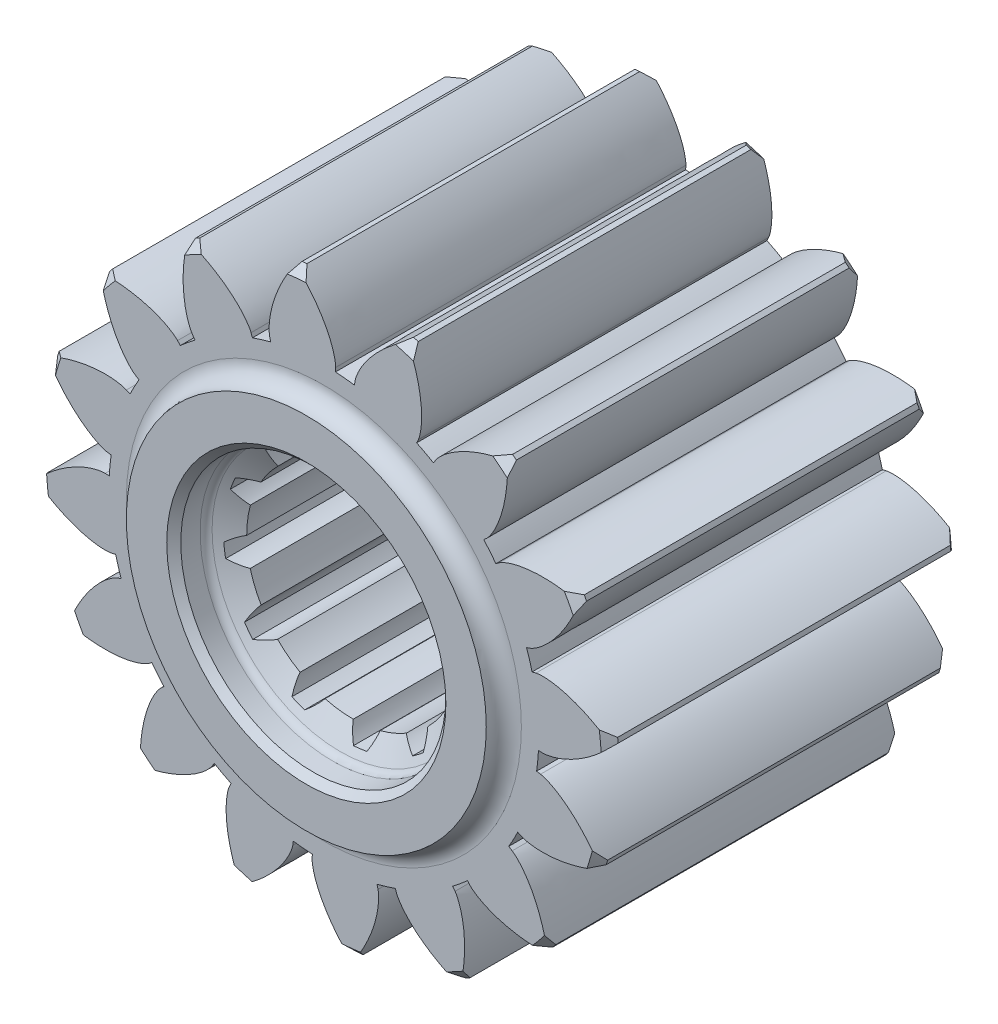
SolidWorks part; units mm, degrees
ref_plane "Front Plane" through (0, 0, 0) normal (0, 0, 1) x (1, 0, 0)
ref_plane "Top Plane" through (0, 0, 0) normal (0, 1, 0) x (1, 0, 0)
ref_plane "Right Plane" through (0, 0, 0) normal (1, 0, 0) x (0, 0, -1)
sketch "Sketch1" plane through (0, 0, 0) normal (1, 0, 0) x (0, 0, -1)
  line L0 (0, 0) -> (43.9, 0) construction
  line L1 (0, 15.9) -> (0, 20.5)
  line L2 (2, 22.5) -> (2, 31.65)
  line L3 (3, 32.65) -> (40.9, 32.65)
  line L4 (41.9, 31.65) -> (41.9, 22.5)
  line L5 (43.9, 20.5) -> (43.9, 15.9)
  line L6 (2, 31.65) -> (3, 32.65)
  line L7 (41.9, 31.65) -> (40.9, 32.65)
  line L8 (0.8, 15.1) -> (3, 15.1)
  line L10 (5.3094, 12.1) -> (38.5906, 12.1)
  line L12 (40.9, 15.1) -> (43.1, 15.1)
  line L13 (0, 15.9) -> (0.8, 15.1)
  line L14 (43.1, 15.1) -> (43.9, 15.9)
  line L15 (3.866, 14.6) -> (5.3094, 12.1)
  line L16 (40.034, 14.6) -> (38.5906, 12.1)
  arc A0 (0, 20.5) -> (2, 22.5) centre (0, 22.5) ccw
  arc A1 (41.9, 22.5) -> (43.9, 20.5) centre (43.9, 22.5) ccw
  arc A2 (3.866, 14.6) -> (3, 15.1) centre (3, 14.1) ccw
  arc A3 (40.9, 15.1) -> (40.034, 14.6) centre (40.9, 14.1) ccw
  dimension "D5" = 2
  dimension "D17" = 1
  dimension "D19" = 3
  dimension "D1" = 43.9
  dimension "D2" = 2
  dimension "D3" = 2
  dimension "D4" = 15.1
  dimension "D6" = 20.5
  dimension "D7" = 32.65
  dimension "D8" = 45
  dimension "D9" = 45
  dimension "D10" = 1
  dimension "D11" = 1
  dimension "D12" = 12.1
  dimension "D13" = 45
  dimension "D14" = 45
  dimension "D15" = 0.8
  dimension "D16" = 0.8
  dimension "D18" = 3
  dimension "D20" = 30
  dimension "D21" = 30
revolve "Revolve1" add sketch "Sketch1" angle 360 about L0
sketch "Sketch2" plane through (0, 0, 0) normal (0, 0, 1) x (1, 0, 0)
  line L0 (0, 0) -> (-1.5655, 11.8974) construction
  arc A0 (-2.5627, 13.5345) -> (-7.7568, 11.3835) centre (0, 0) ccw construction
  arc A1 (3.1074, 11.5907) -> (0, 12) centre (0, 0) ccw construction
  arc A2 (-3.1043, 11.5915) -> (-6, 10.3923) centre (0, 0) ccw construction
  arc A3 (4.5479, 13.0026) -> (-1.0258, 13.7367) centre (0, 0) ccw construction
  arc A4 (8.4864, 8.4842) -> (6, 10.3923) centre (0, 0) ccw construction
  arc A5 (10.4399, 8.9866) -> (5.98, 12.4093) centre (0, 0) ccw construction
  arc A6 (11.5915, 3.1043) -> (10.3923, 6) centre (0, 0) ccw construction
  arc A7 (13.5345, 2.5627) -> (11.3835, 7.7568) centre (0, 0) ccw construction
  arc A8 (11.5907, -3.1074) -> (12, 0) centre (0, 0) ccw construction
  arc A9 (13.0026, -4.5479) -> (13.7367, 1.0258) centre (0, 0) ccw construction
  arc A10 (8.9866, -10.4399) -> (12.4093, -5.98) centre (0, 0) ccw construction
  arc A11 (8.4842, -8.4864) -> (10.3923, -6) centre (0, 0) ccw construction
  arc A12 (3.1043, -11.5915) -> (6, -10.3923) centre (0, 0) ccw construction
  arc A13 (-4.5479, -13.0026) -> (7.7568, -11.3835) centre (0, 0) ccw construction
  arc A14 (-3.1074, -11.5907) -> (0, -12) centre (0, 0) ccw construction
  arc A15 (-8.4864, -8.4842) -> (-6, -10.3923) centre (0, 0) ccw construction
  arc A16 (-10.4399, -8.9866) -> (-5.98, -12.4093) centre (0, 0) ccw construction
  arc A17 (-11.5915, -3.1043) -> (-10.3923, -6) centre (0, 0) ccw construction
  arc A18 (-13.5345, -2.5627) -> (-11.3835, -7.7568) centre (0, 0) ccw construction
  arc A19 (-11.5907, 3.1074) -> (-12, 0) centre (0, 0) ccw construction
  arc A20 (-13.0026, 4.5479) -> (-13.7367, -1.0258) centre (0, 0) ccw construction
  arc A21 (-8.4842, 8.4864) -> (-10.3923, 6) centre (0, 0) ccw construction
  arc A22 (-8.9866, 10.4399) -> (-12.4093, 5.98) centre (0, 0) ccw construction
  circle A23 centre (0, 0) radius 13.775
  circle A24 centre (0, 0) radius 12
  spline S0 degree 3 poles (0, 12) (-0.0366, 12.1032) (-0.1224, 12.3264) (-0.2974, 12.6733) (-0.5245, 13.0595) (-0.7734, 13.4188) (-0.9508, 13.6452) (-1.0258, 13.7367) knots 0.250165 0.250165 0.250165 0.250165 0.360158 0.490165 0.640141 0.810086 0.928975 0.928975 0.928975 0.928975
  spline S1 degree 3 poles (-3.1043, 11.5915) (-3.0956, 11.7007) (-3.0705, 11.9384) (-2.9912, 12.3189) (-2.8717, 12.7507) (-2.7242, 13.1621) (-2.6114, 13.4267) (-2.5627, 13.5345) knots 0.250165 0.250165 0.250165 0.250165 0.360158 0.490165 0.640141 0.810086 0.928975 0.928975 0.928975 0.928975
  spline S2 degree 3 poles (3.1074, 11.5907) (3.1695, 11.6809) (3.3101, 11.8742) (3.569, 12.164) (3.8883, 12.4783) (4.2218, 12.7608) (4.4518, 12.9336) (4.5479, 13.0026) knots 0.250165 0.250165 0.250165 0.250165 0.360158 0.490165 0.640141 0.810086 0.928975 0.928975 0.928975 0.928975
  spline S3 degree 3 poles (6, 10.3923) (6.0199, 10.5) (6.0572, 10.7361) (6.0791, 11.1241) (6.0755, 11.5721) (6.0396, 12.0077) (5.9991, 12.2925) (5.98, 12.4093) knots 0.250165 0.250165 0.250165 0.250165 0.360158 0.490165 0.640141 0.810086 0.928975 0.928975 0.928975 0.928975
  spline S4 degree 3 poles (8.4864, 8.4842) (8.5853, 8.5312) (8.8037, 8.6283) (9.1729, 8.7499) (9.6065, 8.8623) (10.0366, 8.9403) (10.3222, 8.9749) (10.4399, 8.9866) knots 0.250165 0.250165 0.250165 0.250165 0.360158 0.490165 0.640141 0.810086 0.928975 0.928975 0.928975 0.928975
  spline S5 degree 3 poles (10.3923, 6) (10.4633, 6.0833) (10.6138, 6.2692) (10.8267, 6.5942) (11.0476, 6.984) (11.2343, 7.3792) (11.3417, 7.6461) (11.3835, 7.7568) knots 0.250165 0.250165 0.250165 0.250165 0.360158 0.490165 0.640141 0.810086 0.928975 0.928975 0.928975 0.928975
  spline S6 degree 3 poles (11.5915, 3.1043) (11.7007, 3.0956) (11.9384, 3.0705) (12.3189, 2.9912) (12.7507, 2.8717) (13.1621, 2.7242) (13.4267, 2.6114) (13.5345, 2.5627) knots 0.250165 0.250165 0.250165 0.250165 0.360158 0.490165 0.640141 0.810086 0.928975 0.928975 0.928975 0.928975
  spline S7 degree 3 poles (12, 0) (12.1032, 0.0366) (12.3264, 0.1224) (12.6733, 0.2974) (13.0595, 0.5245) (13.4188, 0.7734) (13.6452, 0.9508) (13.7367, 1.0258) knots 0.250165 0.250165 0.250165 0.250165 0.360158 0.490165 0.640141 0.810086 0.928975 0.928975 0.928975 0.928975
  spline S8 degree 3 poles (11.5907, -3.1074) (11.6809, -3.1695) (11.8742, -3.3101) (12.164, -3.569) (12.4783, -3.8883) (12.7608, -4.2218) (12.9336, -4.4518) (13.0026, -4.5479) knots 0.250165 0.250165 0.250165 0.250165 0.360158 0.490165 0.640141 0.810086 0.928975 0.928975 0.928975 0.928975
  spline S9 degree 3 poles (10.3923, -6) (10.5, -6.0199) (10.7361, -6.0572) (11.1241, -6.0791) (11.5721, -6.0755) (12.0077, -6.0396) (12.2925, -5.9991) (12.4093, -5.98) knots 0.250165 0.250165 0.250165 0.250165 0.360158 0.490165 0.640141 0.810086 0.928975 0.928975 0.928975 0.928975
  spline S10 degree 3 poles (8.4842, -8.4864) (8.5312, -8.5853) (8.6283, -8.8037) (8.7499, -9.1729) (8.8623, -9.6065) (8.9403, -10.0366) (8.9749, -10.3222) (8.9866, -10.4399) knots 0.250165 0.250165 0.250165 0.250165 0.360158 0.490165 0.640141 0.810086 0.928975 0.928975 0.928975 0.928975
  spline S11 degree 3 poles (6, -10.3923) (6.0833, -10.4633) (6.2692, -10.6138) (6.5942, -10.8267) (6.984, -11.0476) (7.3792, -11.2343) (7.6461, -11.3417) (7.7568, -11.3835) knots 0.250165 0.250165 0.250165 0.250165 0.360158 0.490165 0.640141 0.810086 0.928975 0.928975 0.928975 0.928975
  spline S12 degree 3 poles (3.1043, -11.5915) (3.0956, -11.7007) (3.0705, -11.9384) (2.9912, -12.3189) (2.8717, -12.7507) (2.7242, -13.1621) (2.6114, -13.4267) (2.5627, -13.5345) knots 0.250165 0.250165 0.250165 0.250165 0.360158 0.490165 0.640141 0.810086 0.928975 0.928975 0.928975 0.928975
  spline S13 degree 3 poles (0, -12) (0.0366, -12.1032) (0.1224, -12.3264) (0.2974, -12.6733) (0.5245, -13.0595) (0.7734, -13.4188) (0.9508, -13.6452) (1.0258, -13.7367) knots 0.250165 0.250165 0.250165 0.250165 0.360158 0.490165 0.640141 0.810086 0.928975 0.928975 0.928975 0.928975
  spline S14 degree 3 poles (-3.1074, -11.5907) (-3.1695, -11.6809) (-3.3101, -11.8742) (-3.569, -12.164) (-3.8883, -12.4783) (-4.2218, -12.7608) (-4.4518, -12.9336) (-4.5479, -13.0026) knots 0.250165 0.250165 0.250165 0.250165 0.360158 0.490165 0.640141 0.810086 0.928975 0.928975 0.928975 0.928975
  spline S15 degree 3 poles (-6, -10.3923) (-6.0199, -10.5) (-6.0572, -10.7361) (-6.0791, -11.1241) (-6.0755, -11.5721) (-6.0396, -12.0077) (-5.9991, -12.2925) (-5.98, -12.4093) knots 0.250165 0.250165 0.250165 0.250165 0.360158 0.490165 0.640141 0.810086 0.928975 0.928975 0.928975 0.928975
  spline S16 degree 3 poles (-8.4864, -8.4842) (-8.5853, -8.5312) (-8.8037, -8.6283) (-9.1729, -8.7499) (-9.6065, -8.8623) (-10.0366, -8.9403) (-10.3222, -8.9749) (-10.4399, -8.9866) knots 0.250165 0.250165 0.250165 0.250165 0.360158 0.490165 0.640141 0.810086 0.928975 0.928975 0.928975 0.928975
  spline S17 degree 3 poles (-10.3923, -6) (-10.4633, -6.0833) (-10.6138, -6.2692) (-10.8267, -6.5942) (-11.0476, -6.984) (-11.2343, -7.3792) (-11.3417, -7.6461) (-11.3835, -7.7568) knots 0.250165 0.250165 0.250165 0.250165 0.360158 0.490165 0.640141 0.810086 0.928975 0.928975 0.928975 0.928975
  spline S18 degree 3 poles (-11.5915, -3.1043) (-11.7007, -3.0956) (-11.9384, -3.0705) (-12.3189, -2.9912) (-12.7507, -2.8717) (-13.1621, -2.7242) (-13.4267, -2.6114) (-13.5345, -2.5627) knots 0.250165 0.250165 0.250165 0.250165 0.360158 0.490165 0.640141 0.810086 0.928975 0.928975 0.928975 0.928975
  spline S19 degree 3 poles (-12, 0) (-12.1032, -0.0366) (-12.3264, -0.1224) (-12.6733, -0.2974) (-13.0595, -0.5245) (-13.4188, -0.7734) (-13.6452, -0.9508) (-13.7367, -1.0258) knots 0.250165 0.250165 0.250165 0.250165 0.360158 0.490165 0.640141 0.810086 0.928975 0.928975 0.928975 0.928975
  spline S20 degree 3 poles (-11.5907, 3.1074) (-11.6809, 3.1695) (-11.8742, 3.3101) (-12.164, 3.569) (-12.4783, 3.8883) (-12.7608, 4.2218) (-12.9336, 4.4518) (-13.0026, 4.5479) knots 0.250165 0.250165 0.250165 0.250165 0.360158 0.490165 0.640141 0.810086 0.928975 0.928975 0.928975 0.928975
  spline S21 degree 3 poles (-10.3923, 6) (-10.5, 6.0199) (-10.7361, 6.0572) (-11.1241, 6.0791) (-11.5721, 6.0755) (-12.0077, 6.0396) (-12.2925, 5.9991) (-12.4093, 5.98) knots 0.250165 0.250165 0.250165 0.250165 0.360158 0.490165 0.640141 0.810086 0.928975 0.928975 0.928975 0.928975
  spline S22 degree 3 poles (-8.4842, 8.4864) (-8.5312, 8.5853) (-8.6283, 8.8037) (-8.7499, 9.1729) (-8.8623, 9.6065) (-8.9403, 10.0366) (-8.9749, 10.3222) (-8.9866, 10.4399) knots 0.250165 0.250165 0.250165 0.250165 0.360158 0.490165 0.640141 0.810086 0.928975 0.928975 0.928975 0.928975
  spline S23 degree 3 poles (-6, 10.3923) (-6.0833, 10.4633) (-6.2692, 10.6138) (-6.5942, 10.8267) (-6.984, 11.0476) (-7.3792, 11.2343) (-7.6461, 11.3417) (-7.7568, 11.3835) knots 0.250165 0.250165 0.250165 0.250165 0.360158 0.490165 0.640141 0.810086 0.928975 0.928975 0.928975 0.928975
  point P146 (0, 0)
  dimension "D1" = 27.55
  dimension "D2" = 1.57
extrude "Cut-Extrude1" cut sketch "Sketch2" against normal through all contours A24 S23 A23 S22 | A24 S21 A23 S20 | A24 S19 A23 S18 | A24 S17 A23 S16 | A24 S15 A23 S14 | A24 S13 A23 S12 | A24 S11 A23 S10 | A24 S9 A23 S8 | A24 S7 A23 S6 | A24 S5 A23 S4 | A24 S3 A23 S2 | S1 A24 S0 A23
sketch "Sketch3" plane through (0, 0, 0) normal (0, 0, 1) x (1, 0, 0)
  line L0 (-23.9037, 28.8) -> (23.9037, 28.8) construction
  line L1 (0, 28.8) -> (21.2128, 41.0472) construction
  line L2 (0, 28.8) -> (-37.797, 6.9779) construction
  line L3 (0, 0) -> (-12.4708, 21.6) construction
  line L4 (0, 0) -> (0, 28.8) construction
  line L5 (0, 0) -> (-7.1956, 23.881) construction
  line L6 (0, 0) -> (-4.3963, 24.551) construction
  line L7 (0, 0) -> (-9.8991, 22.893) construction
  line L8 (0, 0) -> (-1.5384, 24.894) construction
  line L9 (0, 0) -> (1.34, 24.9055) construction
  line L10 (-9.8991, 22.893) -> (0.6747, 27.4652) construction
  line L11 (-7.1956, 23.881) -> (1.077, 26.3737) construction
  line L12 (-4.3963, 24.551) -> (1.2735, 25.5663) construction
  line L13 (-1.5384, 24.894) -> (1.3361, 25.0717) construction
  circle A0 centre (0, 0) radius 28.8 construction
  circle A1 centre (0, 0) radius 24.9415 construction
  point P6 (0, 28.8)
  point P14 (-7.4825, 24.48)
  point P17 (-4.9883, 25.92)
  point P18 (-9.9766, 23.04)
  point P19 (-2.4942, 27.36)
  dimension "D1" = 57.6
  dimension "D2" = 30
  dimension "D3" = 14.4
  dimension "D4" = 2.88
  dimension "D5" = 2.88
  dimension "D6" = 2.88
  dimension "D7" = 2.88
  dimension "D8" = 2.88
  dimension "D9" = 5.76
  dimension "D10" = 8.64
  dimension "D11" = 11.52
  dimension "D17" = 11.52
  dimension "D18" = 8.64
  dimension "D19" = 5.76
  dimension "D20" = 2.88
  dimension "D12" = 2.88
  dimension "D13" = 2.88
  dimension "D14" = 2.88
  dimension "D15" = 2.88
  dimension "D16" = 2.88
sketch "Sketch4" plane through (0, 0, 0) normal (0, 0, 1) x (1, 0, 0)
  line L0 (-14.8763, 20.0194) -> (0, 0) construction
  line L2 (0, 0) -> (-17.0838, 18.1721) construction
  line L3 (-19.0637, 16.0828) -> (0, 0) construction
  line L4 (0, 0) -> (-20.7897, 13.7793) construction
  line L5 (0, 0) -> (-22.2388, 11.2923) construction
  line L6 (0, 28.8) -> (-37.797, 6.9779) construction
  line L7 (-14.8763, 20.0194) -> (-1.0065, 30.326) construction
  line L8 (-17.0838, 18.1721) -> (-2.3954, 31.9807) construction
  line L9 (-19.0637, 16.0828) -> (-4.207, 33.6931) construction
  line L10 (-20.7897, 13.7793) -> (-6.4698, 35.3846) construction
  line L11 (-22.2388, 11.2923) -> (-9.1996, 36.9714) construction
  circle A0 centre (0, 0) radius 24.9415 construction
  circle A1 centre (0, 0) radius 28.8 construction
  point P8 (-24.9415, 14.4)
  point P11 (-22.4474, 15.84)
  point P16 (-19.9532, 17.28)
  point P17 (-17.4591, 18.72)
  point P18 (-14.9649, 20.16)
  dimension "D4" = 2.88
  dimension "D5" = 2.88
  dimension "D6" = 2.88
  dimension "D7" = 2.88
  dimension "D1" = 14.4
  dimension "D2" = 2.88
  dimension "D3" = 2.88
  dimension "D12" = 17.28
  dimension "D13" = 20.16
  dimension "D14" = 23.04
  dimension "D15" = 25.92
  dimension "D16" = 28.8
  dimension "D17" = 17.28
  dimension "D18" = 20.16
  dimension "D19" = 23.04
  dimension "D20" = 25.92
  dimension "D21" = 28.8
  dimension "D8" = 2.88
  dimension "D9" = 2.88
  dimension "D10" = 2.88
  dimension "D11" = 2.88
sketch "Sketch5" plane through (0, 0, 0) normal (0, 0, 1) x (1, 0, 0)
  line L0 (1.3152, 24.4446) -> (1.34, 24.9055)
  line L1 (0, 0) -> (-2.8215, 28.6615) construction
  line L2 (3.4814, 24.2312) -> (3.547, 24.688)
  line L3 (-6.0565, 23.719) -> (-6.1707, 24.1662)
  line L4 (10.5696, 22.0806) -> (10.7689, 22.4969)
  line L5 (12.4893, 21.0544) -> (12.7247, 21.4514)
  line L6 (18.215, 16.355) -> (18.5584, 16.6633)
  line L7 (19.5958, 14.6723) -> (19.9652, 14.9489)
  line L8 (23.0872, 8.1395) -> (23.5225, 8.2929)
  line L9 (23.719, 6.0565) -> (24.1662, 6.1707)
  line L10 (24.4446, -1.3152) -> (24.9055, -1.34)
  line L11 (24.2312, -3.4814) -> (24.688, -3.547)
  line L12 (22.0806, -10.5696) -> (22.4969, -10.7689)
  line L13 (21.0544, -12.4893) -> (21.4514, -12.7247)
  line L14 (16.355, -18.215) -> (16.6633, -18.5584)
  line L15 (14.6723, -19.5958) -> (14.9489, -19.9652)
  line L16 (8.1395, -23.0872) -> (8.2929, -23.5225)
  line L17 (6.0565, -23.719) -> (6.1707, -24.1662)
  line L18 (-1.3152, -24.4446) -> (-1.34, -24.9055)
  line L19 (-3.4814, -24.2312) -> (-3.547, -24.688)
  line L20 (-10.5696, -22.0806) -> (-10.7689, -22.4969)
  line L21 (-12.4893, -21.0544) -> (-12.7247, -21.4514)
  line L22 (-18.215, -16.355) -> (-18.5584, -16.6633)
  line L23 (-19.5958, -14.6723) -> (-19.9652, -14.9489)
  line L24 (-23.0872, -8.1395) -> (-23.5225, -8.2929)
  line L25 (-23.719, -6.0565) -> (-24.1662, -6.1707)
  line L26 (-24.4446, 1.3152) -> (-24.9055, 1.34)
  line L27 (-24.2312, 3.4814) -> (-24.688, 3.547)
  line L28 (-22.0806, 10.5696) -> (-22.4969, 10.7689)
  line L29 (-21.0544, 12.4893) -> (-21.4514, 12.7247)
  line L30 (-16.355, 18.215) -> (-16.6633, 18.5584)
  line L31 (-14.6723, 19.5958) -> (-14.9489, 19.9652)
  line L32 (-8.1395, 23.0872) -> (-8.2929, 23.5225)
  line L33 (0, 0) -> (0, 32.65) construction
  circle A0 centre (0, 0) radius 32.65
  circle A1 centre (0, 0) radius 24.48
  circle A2 centre (0, 0) radius 28.8 construction
  spline S0 degree 3 poles (1.34, 24.9055) (1.3422, 25.1274) (1.2774, 25.6238) (1.063, 26.4852) (0.6532, 27.5769) (-0.0282, 28.9119) (-1.0423, 30.4377) (-2.0639, 31.6476) (-2.7423, 32.3428) (-2.9205, 32.5191) knots 0 0 0 0 0.040002 0.090002 0.160002 0.250002 0.360002 0.490002 0.535233 0.535233 0.535233 0.535233
  spline S1 degree 3 poles (-6.1707, 24.1662) (-6.2161, 24.3833) (-6.2493, 24.8829) (-6.207, 25.7695) (-6.018, 26.9202) (-5.6099, 28.3624) (-4.9128, 30.0567) (-4.1468, 31.4426) (-3.617, 32.2567) (-3.4765, 32.4644) knots 0 0 0 0 0.040002 0.090002 0.160002 0.250002 0.360002 0.490002 0.535233 0.535233 0.535233 0.535233
  spline S2 degree 3 poles (3.547, 24.688) (3.5882, 24.906) (3.7487, 25.3803) (4.1271, 26.1832) (4.742, 27.174) (5.6709, 28.3502) (6.9634, 29.6488) (8.2014, 30.6361) (9.0025, 31.1855) (9.2117, 31.3236) knots 0 0 0 0 0.040002 0.090002 0.160002 0.250002 0.360002 0.490002 0.535233 0.535233 0.535233 0.535233
  spline S3 degree 3 poles (10.7689, 22.4969) (10.8558, 22.701) (10.9859, 23.1845) (11.1175, 24.0623) (11.1567, 25.2278) (11.038, 26.7219) (10.685, 28.5197) (10.2042, 30.0284) (9.8435, 30.9303) (9.7463, 31.1614) knots 0 0 0 0 0.040002 0.090002 0.160002 0.250002 0.360002 0.490002 0.535233 0.535233 0.535233 0.535233
  spline S4 degree 3 poles (12.7247, 21.4514) (12.8462, 21.637) (13.1759, 22.0138) (13.8328, 22.6108) (14.7801, 23.2908) (16.0884, 24.022) (17.7794, 24.7272) (19.3011, 25.1655) (20.2514, 25.3665) (20.4975, 25.4141) knots 0 0 0 0 0.040002 0.090002 0.160002 0.250002 0.360002 0.490002 0.535233 0.535233 0.535233 0.535233
  spline S5 degree 3 poles (18.5584, 16.6633) (18.7168, 16.8187) (19.022, 17.2155) (19.4795, 17.9762) (19.9617, 19.0379) (20.4238, 20.4637) (20.7857, 22.2598) (20.9189, 23.8376) (20.9308, 24.8089) (20.9294, 25.0596) knots 0 0 0 0 0.040002 0.090002 0.160002 0.250002 0.360002 0.490002 0.535233 0.535233 0.535233 0.535233
  spline S6 degree 3 poles (19.9652, 14.9489) (20.1485, 15.074) (20.5973, 15.2959) (21.4326, 15.5961) (22.5681, 15.8618) (24.0566, 16.0367) (25.8887, 16.041) (27.4623, 15.8637) (28.4172, 15.6858) (28.6628, 15.6355) knots 0 0 0 0 0.040002 0.090002 0.160002 0.250002 0.360002 0.490002 0.535233 0.535233 0.535233 0.535233
  spline S7 degree 3 poles (23.5225, 8.2929) (23.7283, 8.3758) (24.1621, 8.6257) (24.8759, 9.1534) (25.7278, 9.9497) (26.7003, 11.0902) (27.7219, 12.611) (28.4488, 14.0178) (28.8315, 14.9106) (28.9261, 15.1428) knots 0 0 0 0 0.040002 0.090002 0.160002 0.250002 0.360002 0.490002 0.535233 0.535233 0.535233 0.535233
  spline S8 degree 3 poles (24.1662, 6.1707) (24.3833, 6.2161) (24.8829, 6.2493) (25.7695, 6.207) (26.9202, 6.018) (28.3624, 5.6099) (30.0567, 4.9128) (31.4426, 4.1468) (32.2567, 3.617) (32.4644, 3.4765) knots 0 0 0 0 0.040002 0.090002 0.160002 0.250002 0.360002 0.490002 0.535233 0.535233 0.535233 0.535233
  spline S9 degree 3 poles (24.9055, -1.34) (25.1274, -1.3422) (25.6238, -1.2774) (26.4852, -1.063) (27.5769, -0.6532) (28.9119, 0.0282) (30.4377, 1.0423) (31.6476, 2.0639) (32.3428, 2.7423) (32.5191, 2.9205) knots 0 0 0 0 0.040002 0.090002 0.160002 0.250002 0.360002 0.490002 0.535233 0.535233 0.535233 0.535233
  spline S10 degree 3 poles (24.688, -3.547) (24.906, -3.5882) (25.3803, -3.7487) (26.1832, -4.1271) (27.174, -4.742) (28.3502, -5.6709) (29.6488, -6.9634) (30.6361, -8.2014) (31.1855, -9.0025) (31.3236, -9.2117) knots 0 0 0 0 0.040002 0.090002 0.160002 0.250002 0.360002 0.490002 0.535233 0.535233 0.535233 0.535233
  spline S11 degree 3 poles (22.4969, -10.7689) (22.701, -10.8558) (23.1845, -10.9859) (24.0623, -11.1175) (25.2278, -11.1567) (26.7219, -11.038) (28.5197, -10.685) (30.0284, -10.2042) (30.9303, -9.8435) (31.1614, -9.7463) knots 0 0 0 0 0.040002 0.090002 0.160002 0.250002 0.360002 0.490002 0.535233 0.535233 0.535233 0.535233
  spline S12 degree 3 poles (21.4514, -12.7247) (21.637, -12.8462) (22.0138, -13.1759) (22.6108, -13.8328) (23.2908, -14.7801) (24.022, -16.0884) (24.7272, -17.7794) (25.1655, -19.3011) (25.3665, -20.2514) (25.4141, -20.4975) knots 0 0 0 0 0.040002 0.090002 0.160002 0.250002 0.360002 0.490002 0.535233 0.535233 0.535233 0.535233
  spline S13 degree 3 poles (16.6633, -18.5584) (16.8187, -18.7168) (17.2155, -19.022) (17.9762, -19.4795) (19.0379, -19.9617) (20.4637, -20.4238) (22.2598, -20.7857) (23.8376, -20.9189) (24.8089, -20.9308) (25.0596, -20.9294) knots 0 0 0 0 0.040002 0.090002 0.160002 0.250002 0.360002 0.490002 0.535233 0.535233 0.535233 0.535233
  spline S14 degree 3 poles (14.9489, -19.9652) (15.074, -20.1485) (15.2959, -20.5973) (15.5961, -21.4326) (15.8618, -22.5681) (16.0367, -24.0566) (16.041, -25.8887) (15.8637, -27.4623) (15.6858, -28.4172) (15.6355, -28.6628) knots 0 0 0 0 0.040002 0.090002 0.160002 0.250002 0.360002 0.490002 0.535233 0.535233 0.535233 0.535233
  spline S15 degree 3 poles (8.2929, -23.5225) (8.3758, -23.7283) (8.6257, -24.1621) (9.1534, -24.8759) (9.9497, -25.7278) (11.0902, -26.7003) (12.611, -27.7219) (14.0178, -28.4488) (14.9106, -28.8315) (15.1428, -28.9261) knots 0 0 0 0 0.040002 0.090002 0.160002 0.250002 0.360002 0.490002 0.535233 0.535233 0.535233 0.535233
  spline S16 degree 3 poles (6.1707, -24.1662) (6.2161, -24.3833) (6.2493, -24.8829) (6.207, -25.7695) (6.018, -26.9202) (5.6099, -28.3624) (4.9128, -30.0567) (4.1468, -31.4426) (3.617, -32.2567) (3.4765, -32.4644) knots 0 0 0 0 0.040002 0.090002 0.160002 0.250002 0.360002 0.490002 0.535233 0.535233 0.535233 0.535233
  spline S17 degree 3 poles (-1.34, -24.9055) (-1.3422, -25.1274) (-1.2774, -25.6238) (-1.063, -26.4852) (-0.6532, -27.5769) (0.0282, -28.9119) (1.0423, -30.4377) (2.0639, -31.6476) (2.7423, -32.3428) (2.9205, -32.5191) knots 0 0 0 0 0.040002 0.090002 0.160002 0.250002 0.360002 0.490002 0.535233 0.535233 0.535233 0.535233
  spline S18 degree 3 poles (-3.547, -24.688) (-3.5882, -24.906) (-3.7487, -25.3803) (-4.1271, -26.1832) (-4.742, -27.174) (-5.6709, -28.3502) (-6.9634, -29.6488) (-8.2014, -30.6361) (-9.0025, -31.1855) (-9.2117, -31.3236) knots 0 0 0 0 0.040002 0.090002 0.160002 0.250002 0.360002 0.490002 0.535233 0.535233 0.535233 0.535233
  spline S19 degree 3 poles (-10.7689, -22.4969) (-10.8558, -22.701) (-10.9859, -23.1845) (-11.1175, -24.0623) (-11.1567, -25.2278) (-11.038, -26.7219) (-10.685, -28.5197) (-10.2042, -30.0284) (-9.8435, -30.9303) (-9.7463, -31.1614) knots 0 0 0 0 0.040002 0.090002 0.160002 0.250002 0.360002 0.490002 0.535233 0.535233 0.535233 0.535233
  spline S20 degree 3 poles (-12.7247, -21.4514) (-12.8462, -21.637) (-13.1759, -22.0138) (-13.8328, -22.6108) (-14.7801, -23.2908) (-16.0884, -24.022) (-17.7794, -24.7272) (-19.3011, -25.1655) (-20.2514, -25.3665) (-20.4975, -25.4141) knots 0 0 0 0 0.040002 0.090002 0.160002 0.250002 0.360002 0.490002 0.535233 0.535233 0.535233 0.535233
  spline S21 degree 3 poles (-18.5584, -16.6633) (-18.7168, -16.8187) (-19.022, -17.2155) (-19.4795, -17.9762) (-19.9617, -19.0379) (-20.4238, -20.4637) (-20.7857, -22.2598) (-20.9189, -23.8376) (-20.9308, -24.8089) (-20.9294, -25.0596) knots 0 0 0 0 0.040002 0.090002 0.160002 0.250002 0.360002 0.490002 0.535233 0.535233 0.535233 0.535233
  spline S22 degree 3 poles (-19.9652, -14.9489) (-20.1485, -15.074) (-20.5973, -15.2959) (-21.4326, -15.5961) (-22.5681, -15.8618) (-24.0566, -16.0367) (-25.8887, -16.041) (-27.4623, -15.8637) (-28.4172, -15.6858) (-28.6628, -15.6355) knots 0 0 0 0 0.040002 0.090002 0.160002 0.250002 0.360002 0.490002 0.535233 0.535233 0.535233 0.535233
  spline S23 degree 3 poles (-23.5225, -8.2929) (-23.7283, -8.3758) (-24.1621, -8.6257) (-24.8759, -9.1534) (-25.7278, -9.9497) (-26.7003, -11.0902) (-27.7219, -12.611) (-28.4488, -14.0178) (-28.8315, -14.9106) (-28.9261, -15.1428) knots 0 0 0 0 0.040002 0.090002 0.160002 0.250002 0.360002 0.490002 0.535233 0.535233 0.535233 0.535233
  spline S24 degree 3 poles (-24.1662, -6.1707) (-24.3833, -6.2161) (-24.8829, -6.2493) (-25.7695, -6.207) (-26.9202, -6.018) (-28.3624, -5.6099) (-30.0567, -4.9128) (-31.4426, -4.1468) (-32.2567, -3.617) (-32.4644, -3.4765) knots 0 0 0 0 0.040002 0.090002 0.160002 0.250002 0.360002 0.490002 0.535233 0.535233 0.535233 0.535233
  spline S25 degree 3 poles (-24.9055, 1.34) (-25.1274, 1.3422) (-25.6238, 1.2774) (-26.4852, 1.063) (-27.5769, 0.6532) (-28.9119, -0.0282) (-30.4377, -1.0423) (-31.6476, -2.0639) (-32.3428, -2.7423) (-32.5191, -2.9205) knots 0 0 0 0 0.040002 0.090002 0.160002 0.250002 0.360002 0.490002 0.535233 0.535233 0.535233 0.535233
  spline S26 degree 3 poles (-24.688, 3.547) (-24.906, 3.5882) (-25.3803, 3.7487) (-26.1832, 4.1271) (-27.174, 4.742) (-28.3502, 5.6709) (-29.6488, 6.9634) (-30.6361, 8.2014) (-31.1855, 9.0025) (-31.3236, 9.2117) knots 0 0 0 0 0.040002 0.090002 0.160002 0.250002 0.360002 0.490002 0.535233 0.535233 0.535233 0.535233
  spline S27 degree 3 poles (-22.4969, 10.7689) (-22.701, 10.8558) (-23.1845, 10.9859) (-24.0623, 11.1175) (-25.2278, 11.1567) (-26.7219, 11.038) (-28.5197, 10.685) (-30.0284, 10.2042) (-30.9303, 9.8435) (-31.1614, 9.7463) knots 0 0 0 0 0.040002 0.090002 0.160002 0.250002 0.360002 0.490002 0.535233 0.535233 0.535233 0.535233
  spline S28 degree 3 poles (-21.4514, 12.7247) (-21.637, 12.8462) (-22.0138, 13.1759) (-22.6108, 13.8328) (-23.2908, 14.7801) (-24.022, 16.0884) (-24.7272, 17.7794) (-25.1655, 19.3011) (-25.3665, 20.2514) (-25.4141, 20.4975) knots 0 0 0 0 0.040002 0.090002 0.160002 0.250002 0.360002 0.490002 0.535233 0.535233 0.535233 0.535233
  spline S29 degree 3 poles (-16.6633, 18.5584) (-16.8187, 18.7168) (-17.2155, 19.022) (-17.9762, 19.4795) (-19.0379, 19.9617) (-20.4637, 20.4238) (-22.2598, 20.7857) (-23.8376, 20.9189) (-24.8089, 20.9308) (-25.0596, 20.9294) knots 0 0 0 0 0.040002 0.090002 0.160002 0.250002 0.360002 0.490002 0.535233 0.535233 0.535233 0.535233
  spline S30 degree 3 poles (-14.9489, 19.9652) (-15.074, 20.1485) (-15.2959, 20.5973) (-15.5961, 21.4326) (-15.8618, 22.5681) (-16.0367, 24.0566) (-16.041, 25.8887) (-15.8637, 27.4623) (-15.6858, 28.4172) (-15.6355, 28.6628) knots 0 0 0 0 0.040002 0.090002 0.160002 0.250002 0.360002 0.490002 0.535233 0.535233 0.535233 0.535233
  spline S31 degree 3 poles (-8.2929, 23.5225) (-8.3758, 23.7283) (-8.6257, 24.1621) (-9.1534, 24.8759) (-9.9497, 25.7278) (-11.0902, 26.7003) (-12.611, 27.7219) (-14.0178, 28.4488) (-14.9106, 28.8315) (-15.1428, 28.9261) knots 0 0 0 0 0.040002 0.090002 0.160002 0.250002 0.360002 0.490002 0.535233 0.535233 0.535233 0.535233
  point P340 (0, 0)
  dimension "D1" = 65.3
  dimension "D2" = 48.96
  dimension "D5" = 5.622
  dimension "D3" = 2.826
  dimension "D4" = 16
extrude "Cut-Extrude2" cut sketch "Sketch5" against normal through all contours L2 S2 A0 S0 L0 A1 | S31 L32 A1 L3 S1 A0 | L31 S30 A0 S29 L30 A1 | L29 S28 A0 S27 L28 A1 | L27 S26 A0 S25 L26 A1 | L25 S24 A0 S23 L24 A1 | L23 S22 A0 S21 L22 A1 | L21 S20 A0 S19 L20 A1 | L19 S18 A0 S17 L18 A1 | L17 S16 A0 S15 L16 A1 | L15 S14 A0 S13 L14 A1 | L13 S12 A0 S11 L12 A1 | L11 S10 A0 S9 L10 A1 | L9 S8 A0 S7 L8 A1 | L7 S6 A0 S5 L6 A1 | L5 S4 A0 S3 L4 A1
equation "\"Z\"= 16'No of Teeth"
equation "\"m\"= 3.6'Module"
equation "\"a\"= 30'Pressure angle"
equation "\"d0\"= \"m\" * \"Z\"'Mid diameter"
equation "\"hk\"= \"m\""
equation "\"hf\"= \"m\" * 1.2"
equation "\"da\"= \"d0\" + \"m\" * 2 + 0.5'outer diameter"
equation "\"df\"= \"d0\" - \"hf\" * 2'root diameter"
equation "\"S\"= ( \"m\" * 3.14 ) / 2"
equation "\"D1@Sketch3\"=\"d0\""
equation "\"D2@Sketch3\"=\"a\""
equation "\"D5@Sketch3\"=\"D4@Sketch3\""
equation "\"D6@Sketch3\"=\"D4@Sketch3\""
equation "\"D7@Sketch3\"=\"D4@Sketch3\""
equation "\"D12@Sketch3\"=\"D4@Sketch3\""
equation "\"D13@Sketch3\"=\"D8@Sketch3\""
equation "\"D14@Sketch3\"=\"D8@Sketch3\""
equation "\"D15@Sketch3\"=\"D8@Sketch3\""
equation "\"D16@Sketch3\"=\"D8@Sketch3\""
equation "\"D17@Sketch3\"=\"D11@Sketch3\""
equation "\"D18@Sketch3\"=\"D10@Sketch3\""
equation "\"D19@Sketch3\"=\"D9@Sketch3\""
equation "\"D20@Sketch3\"=\"D4@Sketch3\""
equation "\"D2@Sketch4\"=2.88"
equation "\"D3@Sketch4\"=\"D2@Sketch4\""
equation "\"D4@Sketch4\"=\"D2@Sketch4\""
equation "\"D5@Sketch4\"=\"D2@Sketch4\""
equation "\"D7@Sketch4\"=\"D2@Sketch4\""
equation "\"D8@Sketch4\"=\"D2@Sketch4\""
equation "\"D9@Sketch4\"=\"D2@Sketch4\""
equation "\"D10@Sketch4\"=\"D2@Sketch4\""
equation "\"D11@Sketch4\"=\"D2@Sketch4\""
equation "\"D17@Sketch4\"=\"D12@Sketch4\""
equation "\"D18@Sketch4\"=\"D13@Sketch4\""
equation "\"D19@Sketch4\"=\"D14@Sketch4\""
equation "\"D20@Sketch4\"=\"D15@Sketch4\""
equation "\"D21@Sketch4\"=\"D16@Sketch4\""
equation "\"D1@Sketch5\"=\"da\""
equation "\"D2@Sketch5\"=\"df\""
equation "\"D3@Sketch5\"=\"S\"/2"
